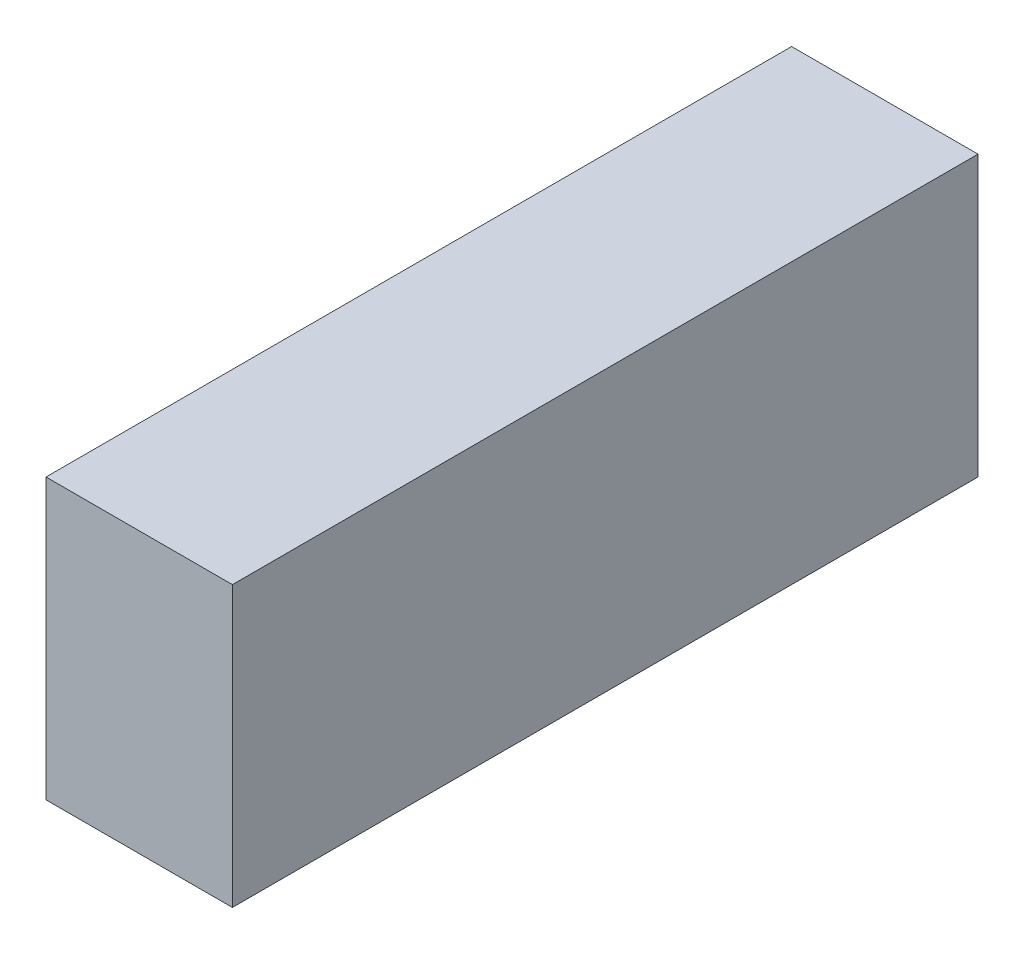
SolidWorks part; units mm, degrees
ref_plane "Front Plane" through (0, 0, 0) normal (0, 0, 1) x (1, 0, 0)
ref_plane "Top Plane" through (0, 0, 0) normal (0, 1, 0) x (1, 0, 0)
ref_plane "Right Plane" through (0, 0, 0) normal (1, 0, 0) x (0, 0, -1)
sketch "Sketch1" plane through (0, 0, 0) normal (0, 0, 1) x (1, 0, 0)
  line L0 (0, 38.1) -> (0, 0)
  line L5 (0, 0) -> (25.4, 0)
  line L6 (25.4, 0) -> (25.4, 38.1)
  line L7 (25.4, 38.1) -> (0, 38.1)
  dimension "D1" = 38.1
  dimension "D2" = 25.4
extrude "Boss-Extrude1" add sketch "Sketch1" along normal blind 101.6
